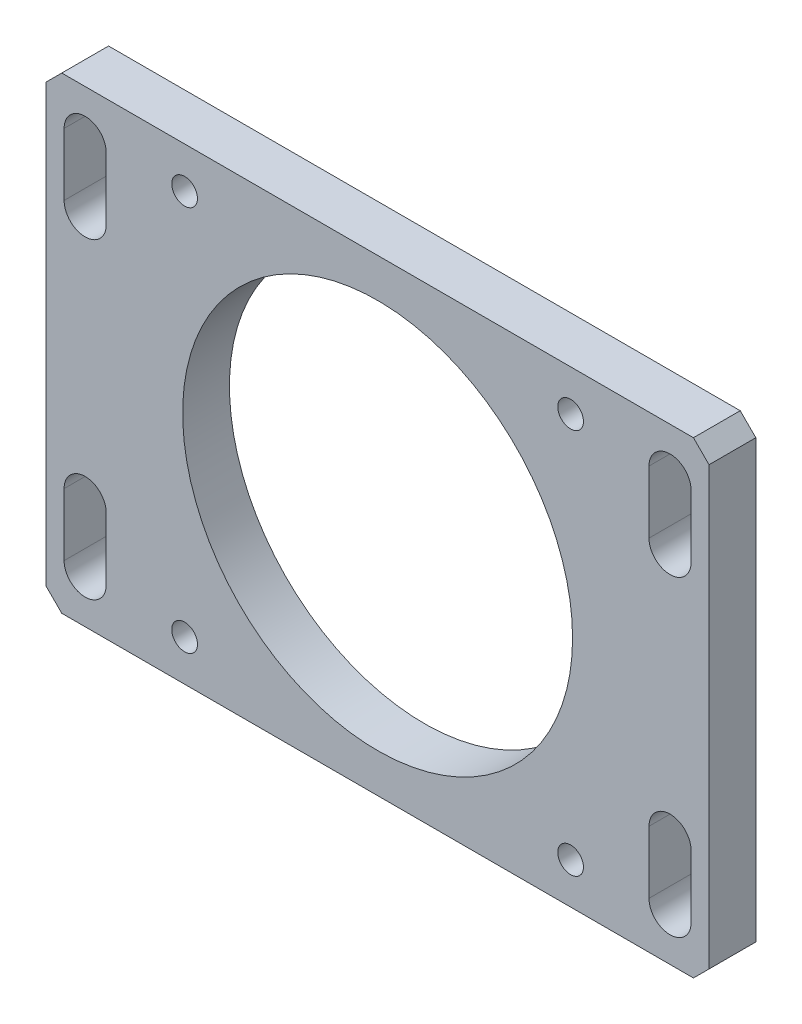
SolidWorks part; units mm, degrees
material "6061"
ref_plane "前视" through (0, 0, 0) normal (0, 0, 1) x (1, 0, 0)
ref_plane "上视" through (0, 0, 0) normal (0, 1, 0) x (1, 0, 0)
ref_plane "右视" through (0, 0, 0) normal (1, 0, 0) x (0, 0, -1)
sketch "草图1" plane through (0, 0, 0) normal (0, 0, 1) x (1, 0, 0)
  line L1 (-42.5, -30) -> (42.5, -30)
  line L2 (-42.5, -30) -> (-42.5, 30)
  line L3 (-42.5, 30) -> (42.5, 30)
  line L4 (42.5, -30) -> (42.5, 30)
  line L5 (-42.5, -30) -> (42.5, 30) construction
  line L6 (-42.5, 30) -> (42.5, -30) construction
  circle A0 centre (0, 0) radius 25
  point P0 (0, 0)
  dimension "D3" = 50
  dimension "D1" = 85
  dimension "D2" = 60
extrude "凸台-拉伸1" add sketch "草图1" along normal blind 6
hole_wizard "M4 螺纹孔1" positions "草图3" profile "草图2" tap size "M4" standard "Iso"
sketch "草图3" plane through (0, 0, 6) normal (0, 0, 1) x (1, 0, 0)
  line L1 (24.7487, 24.7487) -> (0, 0) construction
  line L2 (0, 0) -> (30.3645, 0) construction
  point P1 (24.7487, 24.7487)
  dimension "D1" = 45
  dimension "D2" = 35
sketch "草图2" plane through (24.7487, 24.7487, 6) normal (1, 0, 0) x (0, -1, 0)
  line L0 (0, 0) -> (0, 12.4914)
  line L1 (0, 12.4914) -> (1.65, 11.5)
  line L2 (1.65, 11.5) -> (1.65, 0)
  line L5 (1.65, 0) -> (0, 0)
  line L10 (0, 12.4914) -> (-1.65, 11.5) construction
  line L11 (0, -6.35) -> (0, 107.95) construction
  dimension "螺纹孔钻头直径" = 3.3
  dimension "螺纹孔钻头深度" = 11.5
  dimension "导头角度" = 118
cosmetic thread "孔螺蚊线1" parameters "D1"=6, "D2"=4
pattern_circular "阵列(圆周)1" count 4 over 360 about axis through (0, 0, 0) along (0, 0, 1) of "M4 螺纹孔1"
sketch "草图4" plane through (0, 0, 6) normal (0, 0, 1) x (1, 0, 0)
  line L0 (42.5, 0) -> (0, 0) construction
  line L1 (42.5, -30) -> (42.5, 30) construction
  line L2 (0, 0) -> (0, 30) construction
  line L3 (42.5, 30) -> (-42.5, 30) construction
  line L4 (37.5, 24) -> (37.5, 16) construction
  line L5 (40.2, 24) -> (40.2, 16)
  line L6 (34.8, 24) -> (34.8, 16)
  line L7 (37.5, -24) -> (37.5, -16) construction
  line L8 (40.2, -24) -> (40.2, -16)
  line L9 (34.8, -24) -> (34.8, -16)
  line L10 (-37.5, 24) -> (-37.5, 16) construction
  line L11 (-40.2, 24) -> (-40.2, 16)
  line L12 (-34.8, 24) -> (-34.8, 16)
  line L13 (-37.5, -24) -> (-37.5, -16) construction
  line L14 (-40.2, -24) -> (-40.2, -16)
  line L15 (-34.8, -24) -> (-34.8, -16)
  arc A0 (40.2, 24) -> (34.8, 24) centre (37.5, 24) ccw
  arc A1 (34.8, 16) -> (40.2, 16) centre (37.5, 16) ccw
  arc A2 (40.2, -24) -> (34.8, -24) centre (37.5, -24) cw
  arc A3 (34.8, -16) -> (40.2, -16) centre (37.5, -16) cw
  arc A4 (-40.2, 24) -> (-34.8, 24) centre (-37.5, 24) cw
  arc A5 (-34.8, 16) -> (-40.2, 16) centre (-37.5, 16) cw
  arc A6 (-40.2, -24) -> (-34.8, -24) centre (-37.5, -24) ccw
  arc A7 (-34.8, -16) -> (-40.2, -16) centre (-37.5, -16) ccw
  point P11 (37.5, 20)
  point P18 (37.5, -20)
  point P25 (-37.5, 20)
  point P32 (-37.5, -20)
  dimension "D1" = 2.7
  dimension "D2" = 8
  dimension "D3" = 40
  dimension "D4" = 5
extrude "切除-拉伸1" cut sketch "草图4" against normal blind 6
chamfer "倒角1" distance 2 angle 45 4 edges at (-42.5, -30, 3) (-42.5, 30, 3) (42.5, -30, 3) (42.5, 30, 3)
